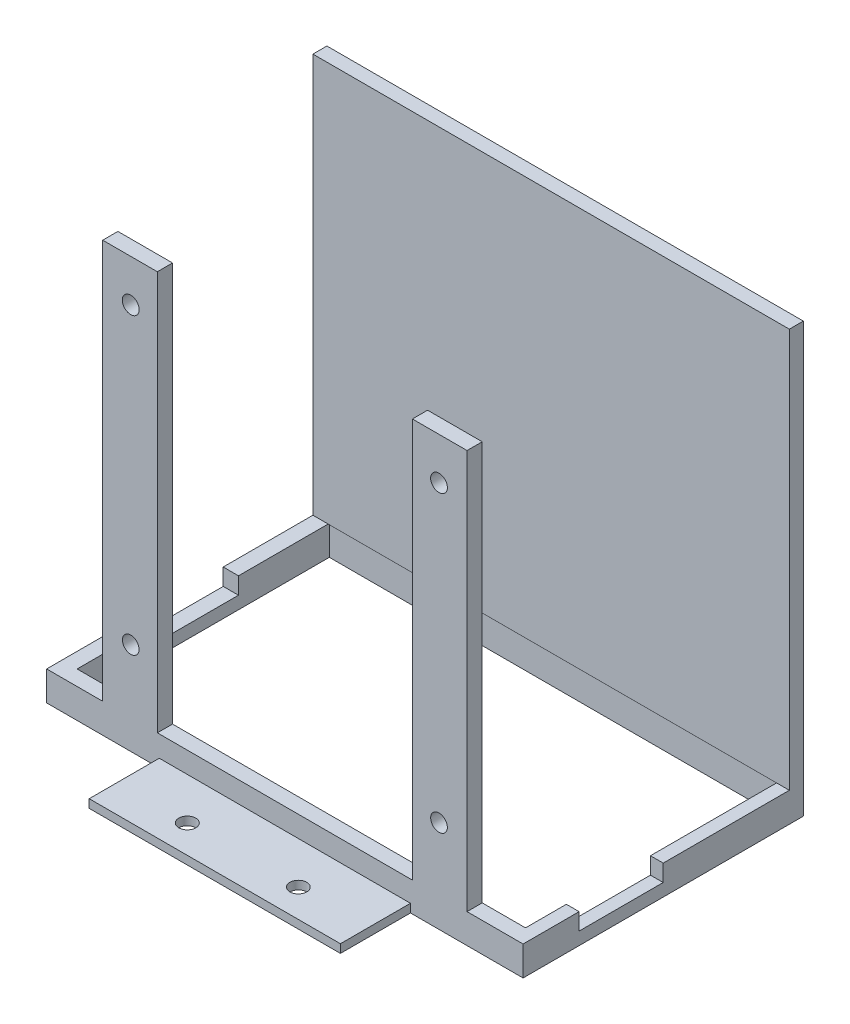
SolidWorks part; units mm, degrees
ref_plane "Front Plane" through (0, 0, 0) normal (0, 0, 1) x (1, 0, 0)
ref_plane "Top Plane" through (0, 0, 0) normal (0, 1, 0) x (1, 0, 0)
ref_plane "Right Plane" through (0, 0, 0) normal (1, 0, 0) x (0, 0, -1)
sketch "Sketch2" plane through (0, 0, 0) normal (0, 0, 1) x (1, 0, 0)
  line L1 (-85, -76.5) -> (85, -76.5)
  line L2 (-85, -76.5) -> (-85, 76.5)
  line L3 (-85, 76.5) -> (85, 76.5)
  line L4 (85, -76.5) -> (85, 76.5)
  line L5 (-85, -76.5) -> (85, 76.5) construction
  line L6 (-85, 76.5) -> (85, -76.5) construction
  point P0 (0, 0)
  dimension "D1" = 153
  dimension "D2" = 170
extrude "Boss-Extrude2" add sketch "Sketch2" along normal blind 5
sketch "Sketch5" plane through (0, 0, 0) normal (1, 0, 0) x (0, 0, -1)
  line L0 (-5, -76.5) -> (-100, -76.5)
  line L3 (-100, -76.5) -> (-100, -65.9923)
  line L4 (-100, -65.9923) -> (-5, -65.9923)
  line L5 (-5, -65.9923) -> (-5, -76.5)
  dimension "D1" = 95
extrude "Boss-Extrude3" add sketch "Sketch5" against normal blind 85 and the other way blind 85
sketch "Sketch6" plane through (0, -65.9923, 0) normal (0, 1, 0) x (1, 0, 0)
  line L5 (-79.5543, -4.5805) -> (80.4457, -4.5805)
  line L6 (-79.5543, -4.5805) -> (-79.5543, -94.5805)
  line L7 (-79.5543, -94.5805) -> (80.4457, -94.5805)
  line L8 (80.4457, -4.5805) -> (80.4457, -94.5805)
  line L9 (-79.5543, -4.5805) -> (80.4457, -94.5805) construction
  line L10 (-79.5543, -94.5805) -> (80.4457, -4.5805) construction
  point P4 (0.4457, -49.5805)
  dimension "D1" = 80
  dimension "D2" = 90
extrude "Cut-Extrude1" cut sketch "Sketch6" against normal through all
sketch "Sketch7" plane through (85, 0, 0) normal (1, 0, 0) x (0, 0, -1)
  line L0 (-80, -65.9923) -> (-80, -71.9923)
  line L1 (-5, -65.9923) -> (-100, -65.9923) construction
  line L2 (-80, -71.9923) -> (-50, -71.9923)
  line L3 (-50, -71.9923) -> (-50, -65.9923)
  line L4 (-50, -65.9923) -> (-80, -65.9923)
  line L5 (-100, -65.9923) -> (-100, -76.5) construction
  dimension "D1" = 20
  dimension "D2" = 30
  dimension "D3" = 6
extrude "Cut-Extrude3" cut sketch "Sketch7" against normal blind 6 and the other way through all
sketch "Sketch12" plane through (-85, 0, 0) normal (-1, 0, 0) x (0, 0, 1)
  line L0 (37, -71.9923) -> (37, -65.9923)
  line L1 (5, -65.9923) -> (100, -65.9923) construction
  line L2 (37, -71.9923) -> (67, -71.9923)
  line L3 (67, -71.9923) -> (67, -65.9923)
  line L4 (67, -65.9923) -> (37, -65.9923)
  dimension "D1" = 6
  dimension "D2" = 30
  dimension "D3" = 32
extrude "Cut-Extrude4" cut sketch "Sketch12" against normal blind 6 and the other way blind 10
sketch "Sketch26" plane through (0, -65.9923, 0) normal (0, 1, 0) x (1, 0, 0)
  line L0 (-79.5543, -94.5805) -> (80.4457, -94.5805) construction
  line L1 (-65, -94.5805) -> (-45.5, -94.5805)
  line L2 (-65, -94.5805) -> (-65, -100)
  line L3 (-65, -100) -> (-45.5, -100)
  line L4 (-45.5, -94.5805) -> (-45.5, -100)
  line L5 (-65, -94.5805) -> (-45.5, -100) construction
  line L6 (-65, -100) -> (-45.5, -94.5805) construction
  line L7 (85, -100) -> (-85, -100) construction
  line L8 (-85, -67) -> (-85, -100) construction
  line L9 (45.5, -94.5805) -> (65, -94.5805)
  line L10 (45.5, -94.5805) -> (45.5, -100)
  line L11 (45.5, -100) -> (65, -100)
  line L12 (65, -94.5805) -> (65, -100)
  line L13 (45.5, -94.5805) -> (65, -100) construction
  line L14 (45.5, -100) -> (65, -94.5805) construction
  line L15 (85, -80) -> (85, -100) construction
  point P4 (-55.25, -97.2902)
  point P13 (55.25, -97.2902)
  dimension "D1" = 20
  dimension "D2" = 39.5
  dimension "D3" = 20
  dimension "D4" = 39.5
extrude "Boss-Extrude5" add sketch "Sketch26" along normal through all
sketch "Sketch27" plane through (0, 0, 100) normal (0, 0, 1) x (1, 0, 0)
  line L0 (85, -76.5) -> (-85, -76.5) construction
  circle A0 centre (-55, -43.5) radius 2.969
  circle A1 centre (-55, 61.5) radius 3.0085
  circle A2 centre (55, 61.5) radius 2.9946
  circle A3 centre (55, -43.5) radius 2.9805
  dimension "D1" = 33
  dimension "D4" = 33
  dimension "D2" = 105
  dimension "D3" = 105
  dimension "D5" = 110
extrude "Cut-Extrude5" cut sketch "Sketch27" against normal blind 10
sketch "Sketch31" plane through (0, 0, 100) normal (0, 0, 1) x (1, 0, 0)
  line L0 (85, -76.5) -> (-85, -76.5) construction
  line L1 (-44.8171, -76.5) -> (44.8171, -76.5)
  line L2 (-44.8171, -76.5) -> (-44.8171, -73.5)
  line L3 (-44.8171, -73.5) -> (44.8171, -73.5)
  line L4 (44.8171, -76.5) -> (44.8171, -73.5)
  line L5 (-44.8171, -76.5) -> (44.8171, -73.5) construction
  line L6 (-44.8171, -73.5) -> (44.8171, -76.5) construction
  line L7 (-85, -65.9923) -> (-85, -76.5) construction
  point P4 (0, -75)
  dimension "D1" = 85
  dimension "D2" = 3
extrude "Boss-Extrude7" add sketch "Sketch31" along normal blind 25
sketch "Sketch32" plane through (0, -73.5, 0) normal (0, 1, 0) x (1, 0, 0)
  line L0 (-44.8171, -125) -> (-44.8171, -100) construction
  line L1 (44.8171, -125) -> (44.8171, -100) construction
  line L2 (45.5, -100) -> (-45.5, -100) construction
  line L3 (44.8171, -100) -> (-44.8171, -100) construction
  circle A0 centre (-19.8171, -115) radius 3.0233
  circle A1 centre (19.8171, -115) radius 2.9951
  dimension "D1" = 25
  dimension "D2" = 25
  dimension "D3" = 15
  dimension "D4" = 15
extrude "Cut-Extrude7" cut sketch "Sketch32" against normal blind 25
sketch "Sketch34" plane through (0, 0, 0) normal (0, 0, -1) x (-1, 0, 0)
  line L0 (85, -76.5) -> (-85, -76.5) construction
  line L1 (-45, -76.5) -> (45, -76.5)
  line L2 (-45, -76.5) -> (-45, -73.5)
  line L3 (-45, -73.5) -> (45, -73.5)
  line L4 (45, -76.5) -> (45, -73.5)
  line L5 (-45, -76.5) -> (45, -73.5) construction
  line L6 (-45, -73.5) -> (45, -76.5) construction
  line L7 (-85, -76.5) -> (-85, 76.5) construction
  point P4 (0, -75)
  dimension "D1" = 90
  dimension "D2" = 3
  dimension "D3" = 85
extrude "Boss-Extrude8" add sketch "Sketch34" along normal blind 25
sketch "Sketch35" plane through (0, -73.5, 0) normal (0, 1, 0) x (1, 0, 0)
  line L0 (-45, 25) -> (-45, 0) construction
  line L1 (45, 25) -> (45, 0) construction
  line L2 (85, 0) -> (-85, 0) construction
  circle A0 centre (-20, 15) radius 3.0399
  circle A1 centre (22.5929, 15) radius 2.976
  dimension "D1" = 25
  dimension "D2" = 22.4071
  dimension "D3" = 15
  dimension "D4" = 15
extrude "Cut-Extrude8" cut sketch "Sketch35" against normal through all
